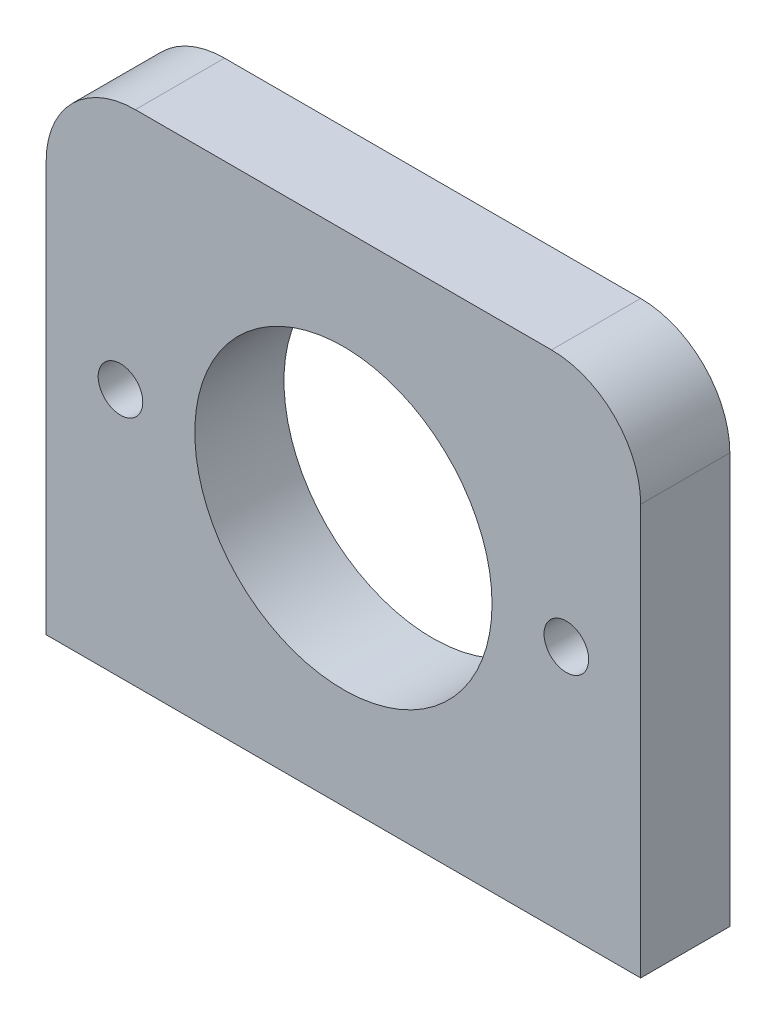
SolidWorks part; units mm, degrees
ref_plane "Front Plane" through (0, 0, 0) normal (0, 0, 1) x (1, 0, 0)
ref_plane "Top Plane" through (0, 0, 0) normal (0, 1, 0) x (1, 0, 0)
ref_plane "Right Plane" through (0, 0, 0) normal (1, 0, 0) x (0, 0, -1)
sketch "Sketch1" plane through (0, 0, 0) normal (0, 0, 1) x (1, 0, 0)
  line L0 (0, 0) -> (-37.5, 0) construction
  line L1 (-50, -42) -> (50, -42)
  line L2 (-50, -42) -> (-50, 27)
  line L3 (-35, 42) -> (35, 42)
  line L4 (50, -42) -> (50, 27)
  line L5 (-50, -42) -> (50, 42) construction
  line L6 (-50, 42) -> (50, -42) construction
  line L7 (0, 0) -> (0, 23.9904) construction
  circle A0 centre (0, 0) radius 25
  arc A1 (35, 42) -> (50, 27) centre (35, 27) cw
  arc A2 (-50, 27) -> (-35, 42) centre (-35, 27) cw
  circle A3 centre (-37.5, 0) radius 3.75
  circle A4 centre (37.5, 0) radius 3.75
  point P0 (0, 0)
  dimension "D1" = 50
  dimension "D4" = 15
  dimension "D6" = 7.5
  dimension "D2" = 42
  dimension "D3" = 100
  dimension "D5" = 37.5
extrude "Boss-Extrude1" add sketch "Sketch1" along normal blind 15
